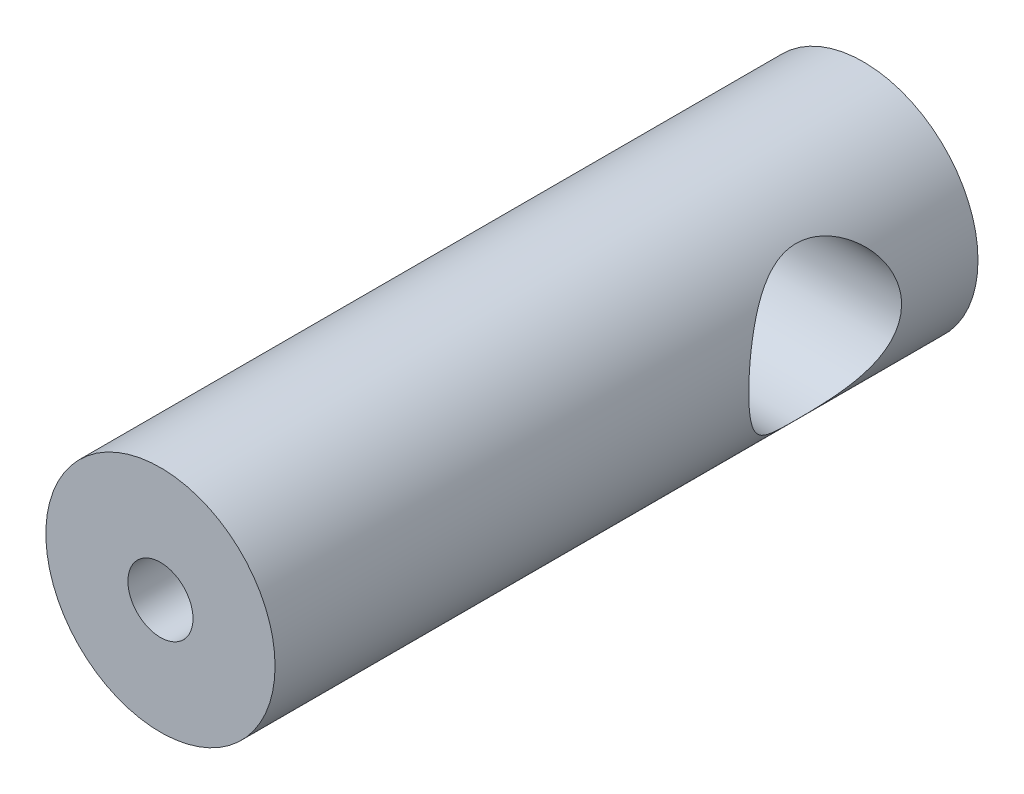
SolidWorks part; units mm, degrees
ref_plane "Front Plane" through (0, 0, 0) normal (0, 0, 1) x (1, 0, 0)
ref_plane "Top Plane" through (0, 0, 0) normal (0, 1, 0) x (1, 0, 0)
ref_plane "Right Plane" through (0, 0, 0) normal (1, 0, 0) x (0, 0, -1)
sketch "Sketch1" plane through (0, 0, 0) normal (0, 0, 1) x (1, 0, 0)
  circle A0 centre (0, 0) radius 4.7625
  dimension "D1" = 9.525
extrude "Boss-Extrude1" add sketch "Sketch1" along normal blind 29.21
sketch "Sketch2" plane through (0, 0, 29.21) normal (0, 0, 1) x (1, 0, 0)
  circle A0 centre (0, 0) radius 1.905
  dimension "D1" = 3.81
extrude "Cut-Extrude1" [suppressed] cut sketch "Sketch2" against normal blind 12.7
sketch "Sketch3" plane through (0, 0, 0) normal (1, 0, 0) x (0, 0, -1)
  line L0 (-29.21, 4.7625) -> (-29.21, -4.7625) construction
  circle A0 centre (-6.35, 0) radius 3.175
  dimension "D2" = 6.35
  dimension "D1" = 22.86
extrude "Cut-Extrude2" cut sketch "Sketch3" against normal through all and the other way through all
hole_wizard "#6-32 Tapped Hole1" positions "Sketch5" profile "Sketch6" tap size "#6-32" standard "ANSI Inch"
sketch "Sketch5" plane through (0, 0, 29.21) normal (0, 0, 1) x (1, 0, 0)
  point P0 (0, 0)
sketch "Sketch6" plane through (0, 0, 29.21) normal (1, 0, 0) x (0, -1, 0)
  line L0 (0, 0) -> (0, 13.5127)
  line L1 (0, 13.5127) -> (1.3525, 12.7)
  line L2 (1.3525, 12.7) -> (1.3525, 0)
  line L5 (1.3525, 0) -> (0, 0)
  line L10 (0, 13.5127) -> (-1.3526, 12.7) construction
  line L11 (0, -6.35) -> (0, 107.95) construction
  dimension "Tap Drill Dia." = 2.7051
  dimension "Tap Drill Depth" = 12.7
  dimension "Drill Angle" = 118
cosmetic thread "Hole Thread1" parameters "D1"=1.0644, "D2"=3.5052
